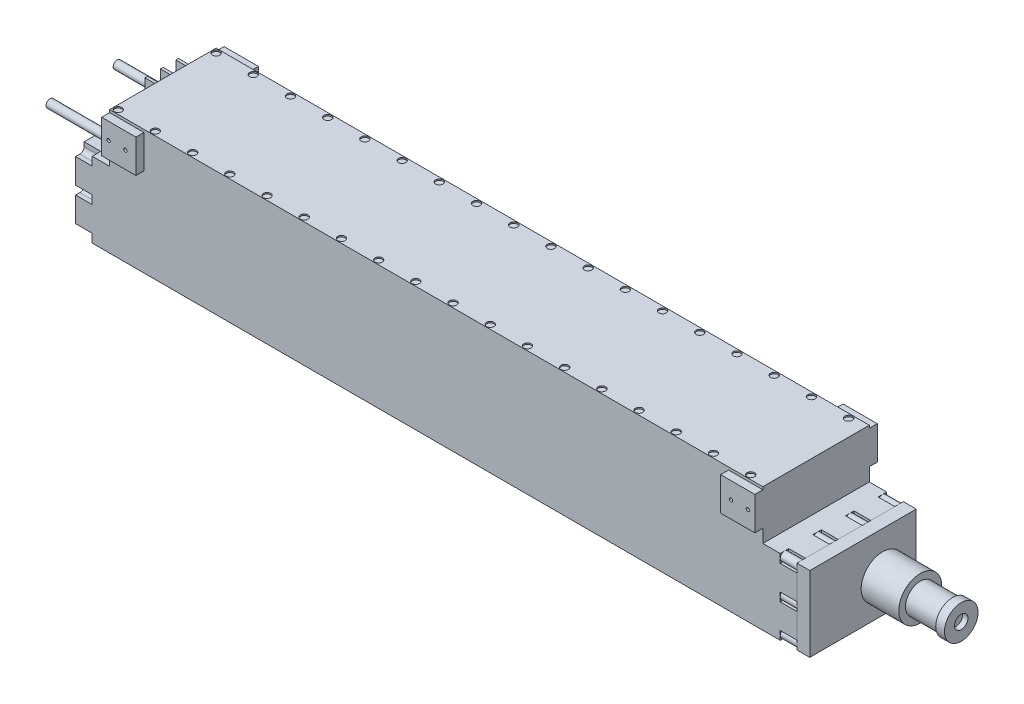
SolidWorks part; units mm, degrees
ref_plane "前视基准面" through (0, 0, 0) normal (0, 0, 1) x (1, 0, 0)
ref_plane "上视基准面" through (0, 0, 0) normal (0, 1, 0) x (1, 0, 0)
ref_plane "右视基准面" through (0, 0, 0) normal (1, 0, 0) x (0, 0, -1)
sketch "草图1" plane through (0, 0, 0) normal (0, 1, 0) x (1, 0, 0)
  line L1 (-243.15, 39.635) -> (243.15, 39.635)
  line L2 (-243.15, 39.635) -> (-243.15, -39.635)
  line L3 (-243.15, -39.635) -> (243.15, -39.635)
  line L4 (243.15, 39.635) -> (243.15, -39.635)
  line L5 (-243.15, 39.635) -> (243.15, -39.635) construction
  line L6 (-243.15, -39.635) -> (243.15, 39.635) construction
  point P0 (0, 0)
  dimension "D1" = 486.3
  dimension "D2" = 79.27
extrude "凸台-拉伸1" add sketch "草图1" along normal blind 36.6
sketch "草图2" plane through (-243.15, 0, 0) normal (-1, 0, 0) x (0, 0, 1)
  line L0 (-28.435, 19.4) -> (6.065, 19.4)
  line L1 (-28.435, 27.4) -> (6.065, 27.4)
  line L2 (-39.635, 36.6) -> (39.635, 36.6) construction
  line L3 (-39.635, 36.6) -> (-39.635, 0) construction
  arc A0 (-28.435, 27.4) -> (-28.435, 19.4) centre (-28.435, 23.4) ccw
  arc A1 (6.065, 19.4) -> (6.065, 27.4) centre (6.065, 23.4) ccw
  dimension "D1" = 4
  dimension "D2" = 34.5
  dimension "D3" = 9.2
  dimension "D4" = 11.2
extrude "凸台-拉伸2" add sketch "草图2" along normal blind 2
sketch "草图3" plane through (-243.15, 0, 0) normal (-1, 0, 0) x (0, 0, 1)
  line L0 (-28.435, 23.4) -> (6.065, 23.4) construction
  line L1 (-23.685, 31.9) -> (-21.685, 31.9)
  line L2 (-23.685, 31.9) -> (-23.685, 14.9)
  line L3 (-23.685, 14.9) -> (-21.685, 14.9)
  line L4 (-21.685, 31.9) -> (-21.685, 14.9)
  line L5 (-23.685, 31.9) -> (-21.685, 14.9) construction
  line L6 (-23.685, 14.9) -> (-21.685, 31.9) construction
  point P0 (-22.685, 23.4)
  dimension "D1" = 2
  dimension "D2" = 17
  dimension "D3" = 4.75
extrude "凸台-拉伸3" add sketch "草图3" along normal blind 12
pattern_linear "阵列(线性)1" count 3 spacing 11.5 along (0, 0, 1) of "凸台-拉伸3"
sketch "草图4" plane through (-245.15, 0, 0) normal (-1, 0, 0) x (0, 0, 1)
  circle A0 centre (-28.435, 23.4) radius 2.15
  dimension "D1" = 4.3
extrude "切除-拉伸1" cut sketch "草图4" against normal blind 1
pattern_linear "阵列(线性)2" count 4 spacing 11.5 along (0, 0, 1) of "切除-拉伸1"
sketch "草图5" plane through (0, 36.6, 0) normal (0, 1, 0) x (1, 0, 0)
  line L6 (243.15, 39.635) -> (-243.15, 39.635) construction
  line L7 (-243.15, 39.635) -> (-243.15, -39.635) construction
  circle A0 centre (-239.95, 36.435) radius 2.75
  dimension "D1" = 5.5
  dimension "D2" = 3.2
  dimension "D3" = 3.2
extrude "切除-拉伸4" cut sketch "草图5" against normal blind 1
pattern_linear "阵列(线性)3" count 18 spacing 27.7 along (1, 0, 0) of "切除-拉伸4"
mirror "镜向1" about plane through (0, 0, 0) normal (0, 0, 1) of "阵列(线性)3", "切除-拉伸4"
sketch "草图6" plane through (0, 0, 0) normal (0, -1, 0) x (1, 0, 0)
  line L1 (-268.5, 39.635) -> (268.5, 39.635)
  line L2 (-268.5, 39.635) -> (-268.5, -39.635)
  line L3 (-268.5, -39.635) -> (268.5, -39.635)
  line L4 (268.5, 39.635) -> (268.5, -39.635)
  line L5 (-268.5, 39.635) -> (268.5, -39.635) construction
  line L6 (-268.5, -39.635) -> (268.5, 39.635) construction
  point P0 (0, 0)
  dimension "D1" = 537
  dimension "D2" = 79.27
extrude "凸台-拉伸4" add sketch "草图6" along normal blind 56
sketch "草图7" plane through (-268.5, 0, 0) normal (-1, 0, 0) x (0, 0, 1)
  line L0 (-15.3183, -3.175) -> (-15.3183, 0)
  line L1 (-39.635, 0) -> (-33.285, 0)
  line L2 (-39.635, 0) -> (-39.635, -6.35)
  line L3 (-39.635, -6.35) -> (-36.46, -6.35)
  line L4 (-33.285, 0) -> (-33.285, -3.175)
  line L5 (39.635, 0) -> (-39.635, 0) construction
  line L6 (-8.9683, -3.175) -> (-8.9683, 0)
  line L7 (-39.635, 0) -> (39.635, 0) construction
  line L8 (8.9984, -3.175) -> (8.9984, 0)
  line L9 (15.3484, -3.175) -> (15.3484, 0)
  line L10 (39.635, 0) -> (39.635, -6.35)
  line L11 (39.635, -56) -> (39.635, 0) construction
  line L12 (33.285, -3.175) -> (33.285, 0)
  line L13 (39.635, -6.35) -> (36.46, -6.35)
  line L14 (33.285, 0) -> (39.635, 0)
  line L15 (-36.46, -24.825) -> (-39.635, -24.825)
  line L16 (-39.635, -56) -> (-39.635, 0) construction
  line L17 (-36.46, -31.175) -> (-39.635, -31.175)
  line L18 (36.46, -24.825) -> (39.635, -24.825)
  line L19 (36.46, -31.175) -> (39.635, -31.175)
  line L20 (-15.3183, 0) -> (-8.9683, 0)
  line L21 (8.9984, 0) -> (15.3484, 0)
  line L22 (39.635, -24.825) -> (39.635, -31.175)
  line L23 (-39.635, -31.175) -> (-39.635, -24.825)
  arc A1 (-36.46, -6.35) -> (-33.285, -3.175) centre (-36.46, -3.175) ccw
  arc A2 (-15.3183, -3.175) -> (-8.9683, -3.175) centre (-12.1433, -3.175) ccw
  arc A3 (8.9984, -3.175) -> (15.3484, -3.175) centre (12.1734, -3.175) ccw
  arc A4 (33.285, -3.175) -> (36.46, -6.35) centre (36.46, -3.175) ccw
  arc A5 (-36.46, -31.175) -> (-36.46, -24.825) centre (-36.46, -28) ccw
  arc A6 (36.46, -24.825) -> (36.46, -31.175) centre (36.46, -28) ccw
  dimension "D3" = 6.35
  dimension "D4" = 6.35
  dimension "D5" = 6.35
  dimension "D6" = 6.35
  dimension "D1" = 6.35
  dimension "D2" = 24.825
  dimension "D7" = 24.3167
  dimension "D8" = 24.3167
extrude "切除-拉伸5" cut sketch "草图7" against normal blind 12.4
ref_plane "基准面1" through (0, -28, 0) normal (0, 1, 0) x (1, 0, 0)
mirror "镜向2" about plane through (0, -28, 0) normal (0, 1, 0) of "切除-拉伸5"
mirror "镜向3" about plane through (0, 0, 0) normal (1, 0, 0) of "镜向2", "切除-拉伸5"
sketch "草图8" plane through (-243.15, 0, 0) normal (-1, 0, 0) x (0, 0, 1)
  line L0 (-39.635, 36.6) -> (39.635, 36.6) construction
  line L1 (-45.5777, 34.6) -> (-39.5777, 34.6)
  line L2 (-45.5777, 34.6) -> (-45.5777, 9.8)
  line L3 (-45.5777, 9.8) -> (-39.5777, 9.8)
  line L4 (-39.5777, 34.6) -> (-39.5777, 9.8)
  line L5 (0, -50.93) -> (0, 50.93) construction
  line L6 (45.5777, 9.8) -> (39.5777, 9.8)
  line L7 (39.5777, 34.6) -> (39.5777, 9.8)
  line L8 (45.5777, 34.6) -> (39.5777, 34.6)
  line L9 (45.5777, 34.6) -> (45.5777, 9.8)
  dimension "D1" = 6
  dimension "D2" = 24.8
  dimension "D3" = 2
extrude "凸台-拉伸5" add sketch "草图8" against normal blind 25.5
sketch "草图9" plane through (0, 0, -45.5777) normal (0, 0, -1) x (-1, 0, 0)
  line L0 (225.45, 22.2) -> (237.95, 22.2) construction
  line L1 (243.15, 34.6) -> (243.15, 9.8) construction
  line L2 (217.65, 34.6) -> (243.15, 34.6) construction
  dimension "D1" = 12.5
  dimension "D2" = 5.2
  dimension "D3" = 12.4
hole_wizard "M3 螺纹孔1" positions "草图10" profile "草图11" tap size "M3" standard "GB" end condition through all
sketch "草图10" plane through (0, 0, -45.5777) normal (0, 0, -1) x (-1, 0, 0)
  point P0 (225.45, 22.2)
  point P3 (237.95, 22.2)
sketch "草图11" plane through (-225.45, 22.2, -45.5777) normal (1, 0, 0) x (0, 1, 0)
  line L0 (0, 0) -> (0, 91.1554)
  line L1 (0, 91.1554) -> (1.25, 91.1554)
  line L2 (1.25, 91.1554) -> (1.25, 0)
  line L5 (1.25, 0) -> (0, 0)
  line L11 (0, -6.35) -> (0, 107.95) construction
  dimension "通孔螺纹孔钻头直径" = 2.5
  dimension "通孔螺纹孔钻头深度" = 91.1554
cosmetic thread "孔螺蚊线1" parameters "D2"=3
cosmetic thread "孔螺蚊线2" parameters "D2"=3
mirror "镜向5" about plane through (0, 0, 0) normal (1, 0, 0) of "M3 螺纹孔1", "凸台-拉伸5"
cosmetic thread "孔螺蚊线3" parameters "D2"=3
cosmetic thread "孔螺蚊线4" parameters "D2"=3
sketch "草图12" plane through (-243.15, 0, 0) normal (-1, 0, 0) x (0, 0, 1)
  line L0 (-25, 3.8) -> (25, 3.8) construction
  line L1 (-39.635, 0) -> (39.635, 0) construction
  line L2 (-39.635, 9.8) -> (-39.635, 0) construction
  circle A1 centre (-25, 3.8) radius 3
  circle A2 centre (25, 3.8) radius 3
  dimension "D4" = 6
  dimension "D5" = 6
  dimension "D1" = 50
  dimension "D2" = 3.8
  dimension "D3" = 14.635
extrude "凸台-拉伸6" add sketch "草图12" along normal blind 59
ref_plane "基准面2" through (278.1, 0, 0) normal (1, 0, 0) x (0, 0, -1)
sketch "草图13" plane through (278.1, 0, 0) normal (1, 0, 0) x (0, 0, -1)
  line L1 (-39.635, 0) -> (39.635, 0)
  line L2 (-39.635, 0) -> (-39.635, -56)
  line L3 (-39.635, -56) -> (39.635, -56)
  line L4 (39.635, 0) -> (39.635, -56)
extrude "凸台-拉伸7" add sketch "草图13" against normal blind 9.6 separate body
ref_plane "基准面3" through (268.5, 0, 0) normal (1, 0, 0) x (0, 0, -1)
sketch "草图14" plane through (268.5, 0, 0) normal (1, 0, 0) x (0, 0, -1)
  circle A0 centre (-36.46, -3.175) radius 3.175
  circle A1 centre (-12.1734, -3.175) radius 3.175
  circle A2 centre (12.1433, -3.175) radius 3.175
  circle A3 centre (36.46, -3.175) radius 3.175
  circle A4 centre (36.46, -28) radius 3.175
  circle A5 centre (36.46, -52.825) radius 3.175
  circle A6 centre (12.1433, -52.825) radius 3.175
  circle A7 centre (-12.1734, -52.825) radius 3.175
  circle A8 centre (-36.46, -52.825) radius 3.175
  circle A9 centre (-36.46, -28) radius 3.175
extrude "凸台-拉伸8" add sketch "草图14" against normal blind 12.4
sketch "草图15" plane through (278.1, 0, 0) normal (1, 0, 0) x (0, 0, -1)
  line L0 (39.635, -56) -> (39.635, 0) construction
  line L1 (-39.635, -56) -> (39.635, -56) construction
  circle A0 centre (14.635, -31) radius 16
  dimension "D3" = 32
  dimension "D1" = 25
  dimension "D2" = 25
extrude "凸台-拉伸9" add sketch "草图15" along normal blind 28
sketch "草图16" plane through (306.1, 0, 0) normal (1, 0, 0) x (0, 0, -1)
  line L0 (-39.635, 36.6) -> (39.635, 36.6) construction
  line L1 (45.5777, 34.6) -> (45.5777, 9.8) construction
  line L2 (39.635, 34.6) -> (45.5777, 34.6) construction
  circle A0 centre (14.635, -31) radius 11
  dimension "D1" = 22
extrude "凸台-拉伸10" add sketch "草图16" along normal blind 24
sketch "草图17" plane through (330.1, 0, 0) normal (1, 0, 0) x (0, 0, -1)
  circle A0 centre (14.635, -31) radius 12.5
  dimension "D1" = 25
extrude "凸台-拉伸11" add sketch "草图17" along normal blind 6.5
sketch "草图18" plane through (336.6, 0, 0) normal (1, 0, 0) x (0, 0, -1)
  circle A0 centre (14.635, -31) radius 5
  dimension "D1" = 10
extrude "切除-拉伸6" cut sketch "草图18" against normal blind 4
